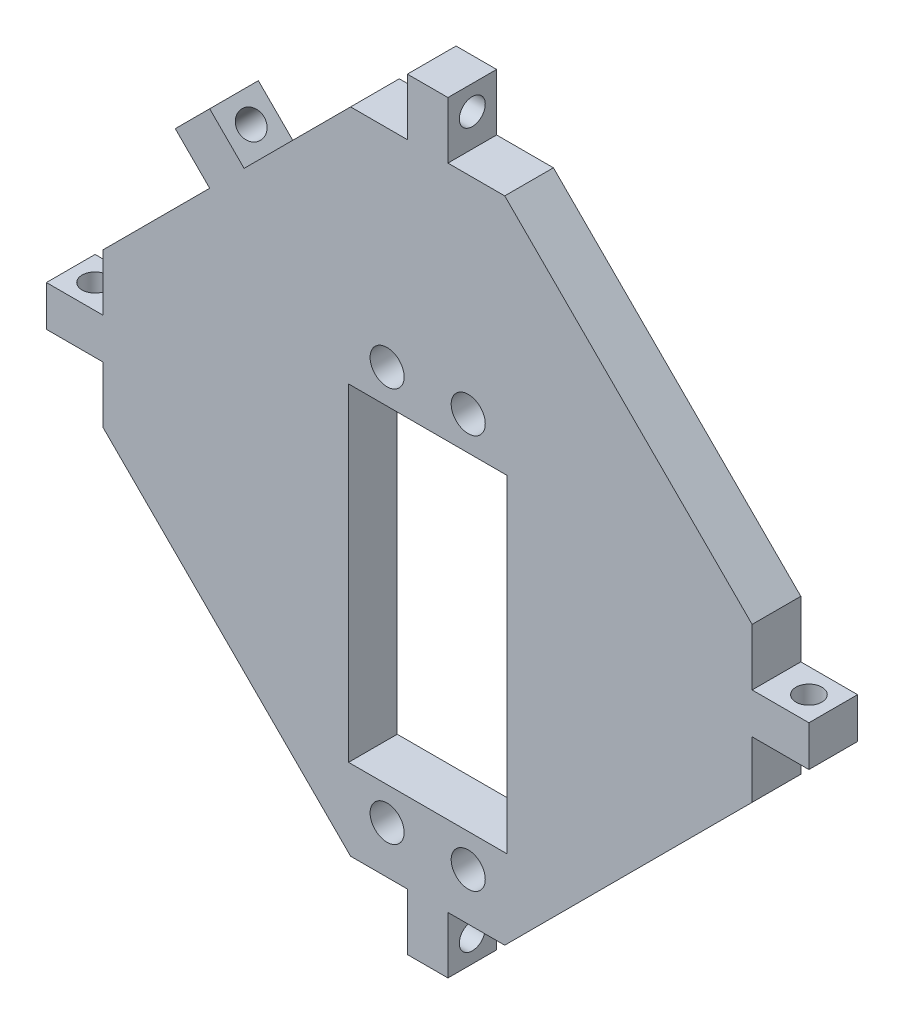
SolidWorks part; units mm, degrees
ref_plane "前视基准面" through (0, 0, 0) normal (0, 0, 1) x (1, 0, 0)
ref_plane "上视基准面" through (0, 0, 0) normal (0, 1, 0) x (1, 0, 0)
ref_plane "右视基准面" through (0, 0, 0) normal (1, 0, 0) x (0, 0, -1)
sketch "草图1" plane through (0, 0, 0) normal (0, 0, 1) x (1, 0, 0)
  line L0 (-49.4975, 0) -> (49.4975, 0) construction
  line L1 (-49.4975, 0) -> (0, 49.4975)
  line L2 (-49.4975, 0) -> (0, -49.4975)
  line L3 (0, -49.4975) -> (49.4975, 0)
  line L4 (0, 49.4975) -> (49.4975, 0)
  line L5 (0, 49.4975) -> (0, -49.4975) construction
  line L6 (-9.5, -39.9975) -> (9.5, -39.9975)
  line L7 (-9.75, 10.3) -> (9.75, 10.3)
  line L8 (-9.75, 10.3) -> (-9.75, -30.1)
  line L9 (-9.75, -30.1) -> (9.75, -30.1)
  line L10 (9.75, 10.3) -> (9.75, -30.1)
  line L11 (-5, 14.465) -> (5, 14.465) construction
  line L12 (-5, 14.465) -> (-5, -34.165) construction
  line L13 (-5, -34.165) -> (5, -34.165) construction
  line L14 (5, 14.465) -> (5, -34.165) construction
  line L15 (-9.75, -30.1) -> (9.75, -30.1)
  line L16 (-9.75, -30.1) -> (-9.75, -36.85)
  line L17 (-9.75, -36.85) -> (9.75, -36.85)
  line L18 (9.75, -30.1) -> (9.75, -36.85)
  line L19 (-2.5, -39.9975) -> (-2.5, -46.9975)
  line L20 (-2.5, -46.9975) -> (2.5, -46.9975)
  line L21 (2.5, -46.9975) -> (2.5, -39.9975)
  line L22 (-39.9975, 9.5) -> (-39.9975, -9.5)
  line L23 (-39.9975, 2.5) -> (-46.9975, 2.5)
  line L24 (-46.9975, 2.5) -> (-46.9975, -2.5)
  line L25 (-46.9975, -2.5) -> (-39.9975, -2.5)
  line L26 (9.5, 39.9975) -> (-9.5, 39.9975)
  line L27 (2.5, 39.9975) -> (2.5, 46.9975)
  line L28 (2.5, 46.9975) -> (-2.5, 46.9975)
  line L29 (-2.5, 46.9975) -> (-2.5, 39.9975)
  line L30 (39.9975, -9.5) -> (39.9975, 9.5)
  line L31 (39.9975, -2.5) -> (46.9975, -2.5)
  line L32 (46.9975, -2.5) -> (46.9975, 2.5)
  line L33 (46.9975, 2.5) -> (39.9975, 2.5)
  circle A0 centre (-5, 14.465) radius 2.1
  circle A1 centre (5, 14.465) radius 2.1
  circle A2 centre (-5, -34.165) radius 2.1
  circle A3 centre (5, -34.165) radius 2.1
  point P19 (0, 0)
  point P25 (0, -46.9975)
  point P49 (0, 0)
  point P288 (0, 0)
  dimension "D7" = 36.85
  dimension "D5" = 70
  dimension "D1" = 19.5
  dimension "D2" = 40.4
  dimension "D3" = 10
  dimension "D4" = 48.63
  dimension "D6" = 4.165
  dimension "D9" = 5
  dimension "D10" = 7
  dimension "D8" = 4
extrude "凸台-拉伸2" add sketch "草图1" along normal blind 6 contours L3 L30 L4 L26 L1 L22 L2 L6 A1 A0 L10 L18 L17 L16 L8 L7 | L28 L29 L26 L27 | L24 L25 L22 L23 | L20 L21 L6 L19 | L32 L33 L30 L31 | L18 L9 L16 L17 A3 A2
sketch "草图2" plane through (0, -2.5, 0) normal (0, -1, 0) x (1, 0, 0)
  line L1 (-46.9975, 6) -> (-40.9975, 6)
  line L2 (-46.9975, 6) -> (-46.9975, 0)
  line L3 (-46.9975, 0) -> (-40.9975, 0)
  line L4 (-40.9975, 6) -> (-40.9975, 0)
  line L5 (-43.9975, 0) -> (-43.9975, 6) construction
  line L6 (-46.9975, 3) -> (-40.9975, 3) construction
  circle A0 centre (-43.9975, 3) radius 1.6
  point P556 (-43.9975, 3)
extrude "切除-拉伸1" cut sketch "草图2" against normal blind 5 contours A0
sketch "草图3" plane through (2.5, 0, 0) normal (1, 0, 0) x (0, 0, -1)
  line L0 (-6, -46.9975) -> (-6, -39.9975) construction
  line L1 (0, -46.9975) -> (-6, -46.9975)
  line L2 (0, -46.9975) -> (0, -40.9975)
  line L3 (0, -40.9975) -> (-6, -40.9975)
  line L4 (-6, -46.9975) -> (-6, -40.9975)
  line L5 (-3, -40.9975) -> (-3, -46.9975) construction
  line L6 (0, -43.9975) -> (-6, -43.9975) construction
  circle A0 centre (-3, -43.9975) radius 1.6
  point P368 (-3, -43.9975)
extrude "切除-拉伸2" cut sketch "草图3" against normal blind 5 contours A0
sketch "草图4" plane through (0, 2.5, 0) normal (0, 1, 0) x (1, 0, 0)
  line L0 (46.9975, -6) -> (39.9975, -6) construction
  line L1 (46.9975, 0) -> (40.9975, 0)
  line L2 (46.9975, 0) -> (46.9975, -6)
  line L3 (46.9975, -6) -> (40.9975, -6)
  line L4 (40.9975, 0) -> (40.9975, -6)
  line L5 (43.9975, -6) -> (43.9975, 0) construction
  line L6 (46.9975, -3) -> (40.9975, -3) construction
  circle A0 centre (43.9975, -3) radius 1.6
  point P136 (43.9975, -3)
extrude "切除-拉伸3" cut sketch "草图4" against normal blind 5 contours A0
sketch "草图5" plane through (-2.5, 0, 0) normal (-1, 0, 0) x (0, 0, 1)
  line L0 (6, 46.9975) -> (6, 39.9975) construction
  line L1 (0, 46.9975) -> (6, 46.9975)
  line L2 (0, 46.9975) -> (0, 40.9975)
  line L3 (0, 40.9975) -> (6, 40.9975)
  line L4 (6, 46.9975) -> (6, 40.9975)
  line L5 (3, 40.9975) -> (3, 46.9975) construction
  line L6 (0, 43.9975) -> (6, 43.9975) construction
  circle A0 centre (3, 43.9975) radius 1.6
  point P192 (3, 43.9975)
extrude "切除-拉伸4" cut sketch "草图5" against normal blind 5 contours A0
sketch "草图6" plane through (0, 0, 6) normal (0, 0, 1) x (1, 0, 0)
  line L1 (-9.5, 39.9975) -> (-39.9975, 9.5)
  line L2 (-24.7487, 24.7487) -> (-28.9914, 28.9914) construction
  line L3 (-26.8701, 31.1127) -> (-31.1127, 26.8701)
  line L4 (-31.1127, 26.8701) -> (-26.8701, 22.6274)
  line L5 (-26.8701, 31.1127) -> (-22.6274, 26.8701)
  point P9 (-28.9914, 28.9914)
  line M24 (-9.5, 39.9975) -> (-39.9975, 9.5)
extrude "凸台-拉伸3" add sketch "草图6" against normal blind 6 contours L2 L3 L4 M24 | L2 L1 L5 L3
sketch "草图7" plane through (-2.1213, -2.1213, 0) normal (-0.7071, -0.7071, 0) x (0, 0, 1)
  line L1 (0, 41) -> (6, 41)
  line L2 (0, 41) -> (0, 35)
  line L3 (0, 35) -> (6, 35)
  line L4 (6, 41) -> (6, 35)
  line L5 (3, 35) -> (3, 41) construction
  line L6 (0, 38) -> (6, 38) construction
  circle A0 centre (3, 38) radius 1.6
  point P212 (3, 38)
extrude "切除-拉伸5" cut sketch "草图7" against normal blind 6 contours A0
